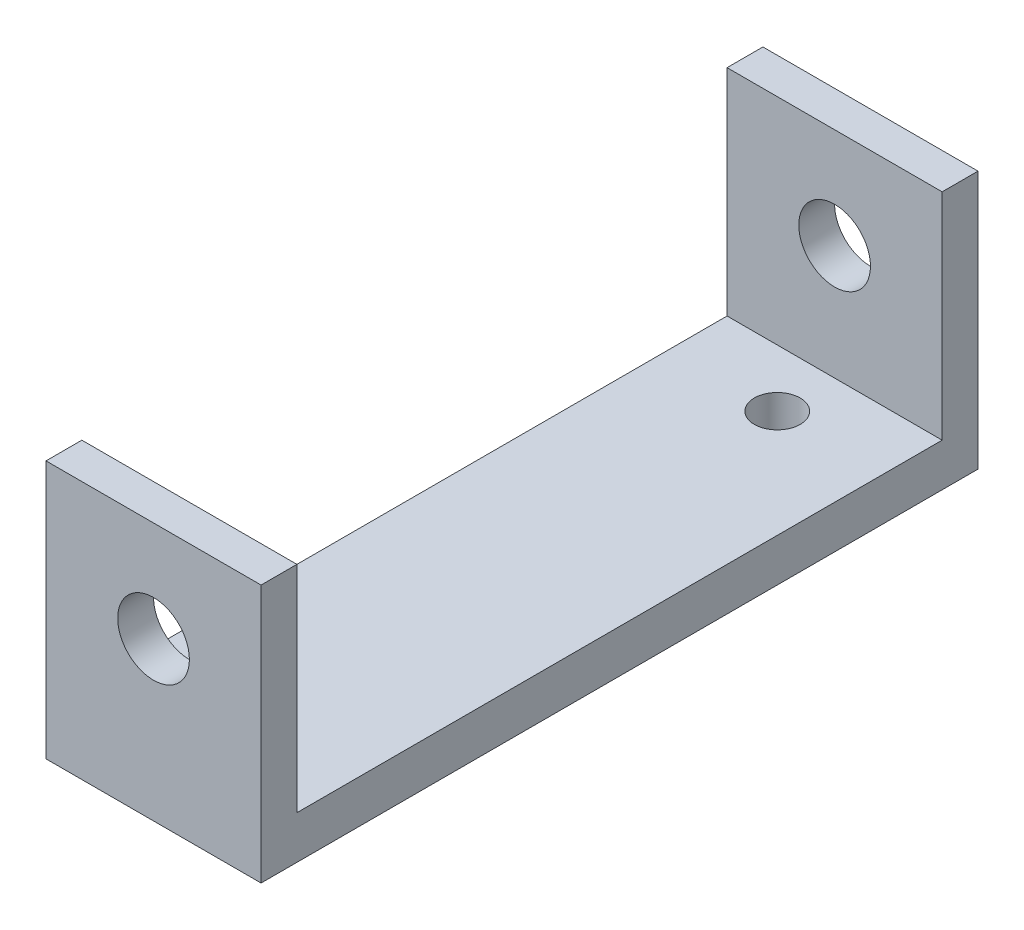
SolidWorks part; units mm, degrees
ref_plane "Plan de face" through (0, 0, 0) normal (0, 0, 1) x (1, 0, 0)
ref_plane "Plan de dessus" through (0, 0, 0) normal (0, 1, 0) x (1, 0, 0)
ref_plane "Plan de droite" through (0, 0, 0) normal (1, 0, 0) x (0, 0, -1)
sketch "Esquisse1" plane through (0, 0, 0) normal (0, 0, 1) x (1, 0, 0)
  line L1 (-124.3779, 32.236) -> (-109.3779, 32.236)
  line L2 (-124.3779, 32.236) -> (-124.3779, 29.236)
  line L3 (-124.3779, 29.236) -> (-109.3779, 29.236)
  line L4 (-109.3779, 32.236) -> (-109.3779, 29.236)
  line L5 (-124.3779, 32.236) -> (-109.3779, 29.236) construction
  line L6 (-124.3779, 29.236) -> (-109.3779, 32.236) construction
  point P0 (-116.8779, 30.736)
  dimension "D1" = 3
  dimension "D2" = 15
extrude "Boss.-Extru.1" add sketch "Esquisse1" along normal blind 50
sketch "Esquisse2" plane through (0, 32.236, 0) normal (0, 1, 0) x (1, 0, 0)
  line L0 (-124.3779, -25) -> (-109.3779, -25) construction
  line L1 (-124.3779, -50) -> (-124.3779, 0) construction
  line L2 (-109.3779, -50) -> (-109.3779, 0) construction
  line L3 (-116.8779, -50) -> (-116.8779, 0) construction
  line L4 (-109.3779, -50) -> (-124.3779, -50) construction
  line L5 (-109.3779, 0) -> (-124.3779, 0) construction
  circle A0 centre (-116.8779, -43.5) radius 1.6
  circle A1 centre (-116.8779, -6.5) radius 1.6
  dimension "D1" = 3.2
  dimension "D2" = 18.5
extrude "Enlèv. mat.-Extru.1" cut sketch "Esquisse2" against normal blind 45
sketch "Esquisse3" plane through (0, 32.236, 0) normal (0, 1, 0) x (1, 0, 0)
  line L0 (-124.3779, -50) -> (-124.3779, 0) construction
  line L1 (-109.3779, -50) -> (-124.3779, -50)
  line L2 (-109.3779, -50) -> (-109.3779, -47.5)
  line L3 (-109.3779, -47.5) -> (-124.3779, -47.5)
  line L4 (-124.3779, -50) -> (-124.3779, -47.5)
  line L6 (-109.3779, 0) -> (-124.3779, 0)
  line L7 (-109.3779, 0) -> (-109.3779, -2.5)
  line L8 (-109.3779, -2.5) -> (-124.3779, -2.5)
  line L9 (-124.3779, 0) -> (-124.3779, -2.5)
  dimension "D1" = 2.5
  dimension "D2" = 2.5
extrude "Boss.-Extru.2" add sketch "Esquisse3" along normal blind 15
sketch "Esquisse4" plane through (0, 0, 50) normal (0, 0, 1) x (1, 0, 0)
  line L0 (-109.3779, 29.236) -> (-109.3779, 47.236) construction
  line L1 (-109.3779, 32.236) -> (-124.3779, 32.236) construction
  line L2 (-109.3779, 38.236) -> (-124.3779, 38.236) construction
  line L3 (-124.3779, 47.236) -> (-124.3779, 29.236) construction
  line L4 (-116.8779, 47.236) -> (-116.8779, 29.236) construction
  line L5 (-124.3779, 47.236) -> (-109.3779, 47.236) construction
  line L6 (-124.3779, 29.236) -> (-109.3779, 29.236) construction
  circle A0 centre (-116.8779, 40.236) radius 2.5
  dimension "D1" = 5
  dimension "D2" = 7.5
  dimension "D3" = 2
  dimension "D4" = 8
extrude "Enlèv. mat.-Extru.3" cut sketch "Esquisse4" against normal blind 65 contours A0
